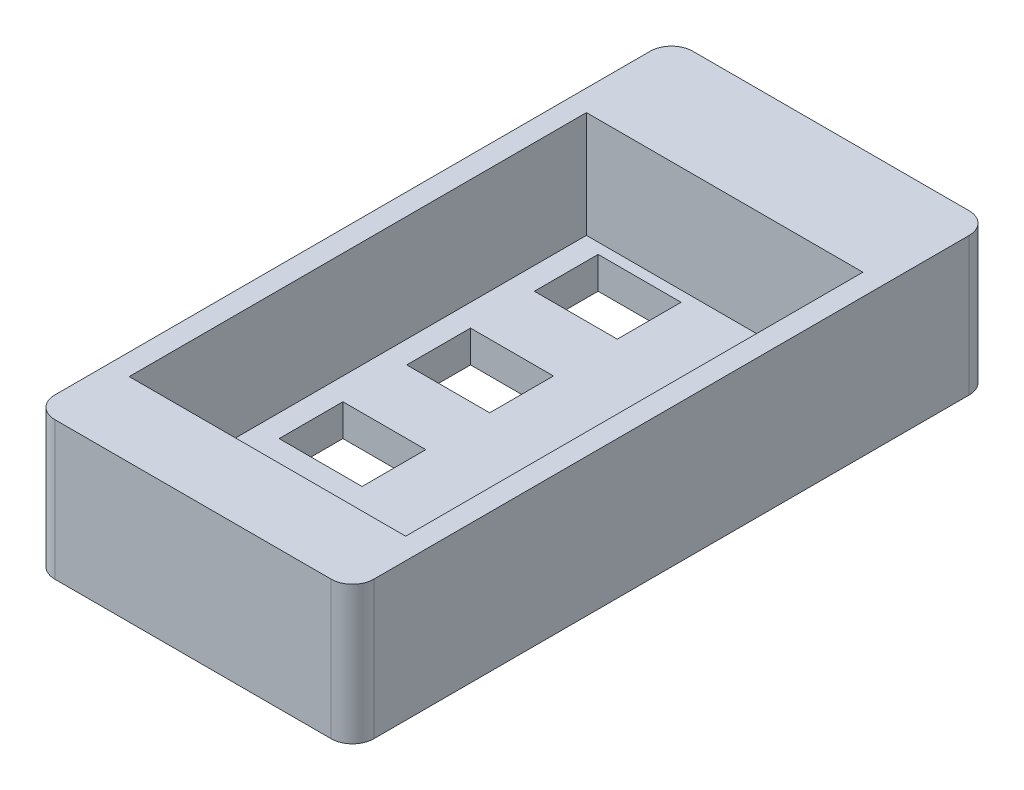
SolidWorks part; units mm, degrees
ref_plane "Front Plane" through (0, 0, 0) normal (0, 0, 1) x (1, 0, 0)
ref_plane "Top Plane" through (0, 0, 0) normal (0, 1, 0) x (1, 0, 0)
ref_plane "Right Plane" through (0, 0, 0) normal (1, 0, 0) x (0, 0, -1)
sketch "Sketch1" plane through (0, 0, 0) normal (0, 1, 0) x (1, 0, 0)
  line L1 (-15, 30) -> (15, 30)
  line L2 (-15, 30) -> (-15, -30)
  line L3 (-15, -30) -> (15, -30)
  line L4 (15, 30) -> (15, -30)
  line L5 (-15, 30) -> (15, -30) construction
  line L6 (-15, -30) -> (15, 30) construction
  point P0 (0, 0)
  dimension "D1" = 30
  dimension "D2" = 60
extrude "Boss-Extrude1" add sketch "Sketch1" along normal blind 3
sketch "Sketch2" plane through (0, 3, 0) normal (0, 1, 0) x (1, 0, 0)
  line L0 (0, 30) -> (0, -30) construction
  line L1 (15, 30) -> (-15, 30) construction
  line L2 (-15, -30) -> (15, -30) construction
  line L3 (-7, 30) -> (-7, -30) construction
  line L4 (-6.4, -16) -> (6.4, -16)
  line L5 (-6.4, -16) -> (-6.4, -22)
  line L6 (-6.4, -22) -> (6.4, -22)
  line L7 (6.4, -16) -> (6.4, -22)
  line L8 (-6.4, -16) -> (6.4, -22) construction
  line L9 (-6.4, -22) -> (6.4, -16) construction
  line L10 (-10.9, 7) -> (-10.9, 1)
  line L11 (-10.9, -5) -> (-3.1, -5)
  line L12 (-10.9, -5) -> (-10.9, -11)
  line L13 (-10.9, -11) -> (-3.1, -11)
  line L14 (-3.1, -5) -> (-3.1, -11)
  line L15 (-10.9, -5) -> (-3.1, -11) construction
  line L16 (-10.9, -11) -> (-3.1, -5) construction
  line L17 (-10.9, 7) -> (-3.1, 7)
  line L18 (-3.1, 7) -> (-3.1, 1)
  line L19 (-10.9, 1) -> (-3.1, 1)
  line L20 (-10.9, 19) -> (-10.9, 13)
  line L21 (-10.9, 19) -> (-3.1, 19)
  line L22 (-3.1, 19) -> (-3.1, 13)
  line L23 (-10.9, 13) -> (-3.1, 13)
  line L24 (10.9, -11) -> (3.1, -11)
  line L25 (3.1, -5) -> (3.1, -11)
  line L26 (10.9, -5) -> (3.1, -5)
  line L27 (10.9, -5) -> (10.9, -11)
  line L28 (10.9, 7) -> (3.1, 7)
  line L29 (3.1, 7) -> (3.1, 1)
  line L30 (10.9, 1) -> (3.1, 1)
  line L31 (10.9, 7) -> (10.9, 1)
  line L32 (10.9, 19) -> (3.1, 19)
  line L33 (3.1, 19) -> (3.1, 13)
  line L34 (10.9, 13) -> (3.1, 13)
  line L35 (10.9, 19) -> (10.9, 13)
  point P6 (0, -19)
  point P13 (-7, -8)
  dimension "D1" = 12.8
  dimension "D2" = 6
  dimension "D3" = 8
  dimension "D4" = 7
  dimension "D5" = 6
  dimension "D6" = 7.8
  dimension "D7" = 5
  dimension "D8" = 3
extrude "Cut-Extrude1" cut sketch "Sketch2" against normal blind 3
sketch "Sketch4" plane through (0, 3, 0) normal (0, 1, 0) x (1, 0, 0)
  line L14 (-13, -28) -> (13, -28)
  line L15 (13, -28) -> (13, 28)
  line L16 (13, 28) -> (-13, 28)
  line L17 (-13, 28) -> (-13, -28)
  line L18 (-13, -28) -> (13, -28)
  line L19 (13, -28) -> (13, 28)
  line L20 (13, 28) -> (-13, 28)
  line L21 (-13, 28) -> (-13, -28)
  line L22 (15, -30) -> (15, 30)
  line L23 (15, 30) -> (-15, 30)
  line L24 (-15, 30) -> (-15, -30)
  line L25 (-15, -30) -> (15, -30)
  line L26 (15, -30) -> (15, 30)
  line L27 (15, 30) -> (-15, 30)
  line L28 (-15, 30) -> (-15, -30)
  line L29 (-15, -30) -> (15, -30)
  dimension "D1" = 2
  dimension "D2" = 0
extrude "Boss-Extrude2" add sketch "Sketch4" along normal blind 10
sketch "Sketch5" plane through (0, 3, 0) normal (0, 1, 0) x (1, 0, 0)
  line L0 (-13, 20) -> (13, 20)
  line L1 (-13, 28) -> (-13, -28) construction
  line L2 (13, -28) -> (13, 28) construction
  line L3 (-13, -23) -> (13, -23)
  line L4 (-13, 28) -> (-13, -28) construction
  line L5 (13, -28) -> (13, 28) construction
  line L6 (13, -23) -> (13, -28)
  line L7 (13, -28) -> (-13, -28)
  line L8 (-13, -28) -> (-13, -23)
  line L9 (-13, 20) -> (-13, 28)
  line L10 (-13, 28) -> (13, 28)
  line L11 (13, 28) -> (13, 20)
  dimension "D1" = 8
  dimension "D2" = 5
extrude "Boss-Extrude3" add sketch "Sketch5" along normal blind 10
fillet "Fillet1" radius 2 4 edges at (-15, 6.5, 30) (15, 6.5, 30) (15, 6.5, -30) (-15, 6.5, -30)
